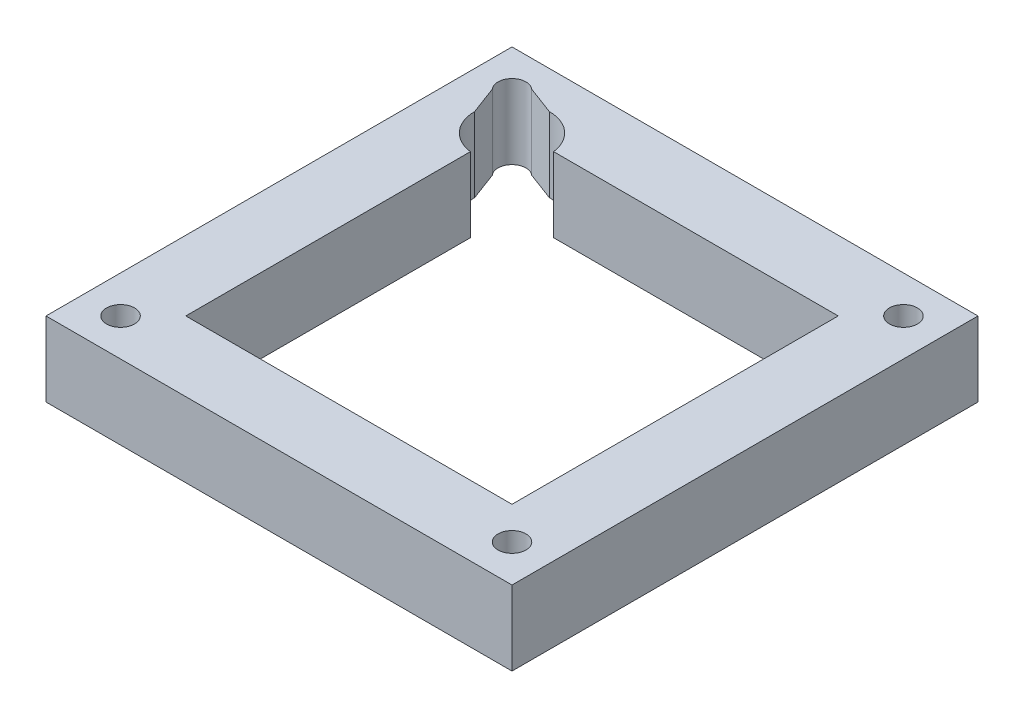
SolidWorks part; units mm, degrees
ref_plane "Front Plane" through (0, 0, 0) normal (0, 0, 1) x (1, 0, 0)
ref_plane "Top Plane" through (0, 0, 0) normal (0, 1, 0) x (1, 0, 0)
ref_plane "Right Plane" through (0, 0, 0) normal (1, 0, 0) x (0, 0, -1)
sketch "Sketch1" plane through (0, 0, 0) normal (0, 1, 0) x (1, 0, 0)
  line L0 (17.5, 17.5) -> (-13.0314, 17.5)
  line L1 (-25, -25) -> (25, -25)
  line L2 (-25, -25) -> (-25, 25)
  line L3 (-25, 25) -> (25, 25)
  line L4 (25, -25) -> (25, 25)
  line L5 (0, 25) -> (0, -25) construction
  line L6 (-25, 0) -> (25, 0) construction
  line L11 (0, 20) -> (0, -20) construction
  line L12 (-20, 0) -> (20, 0) construction
  line L13 (-17.5, -17.5) -> (17.5, -17.5)
  line L16 (17.5, -17.5) -> (17.5, 17.5)
  line L17 (0, 17.5) -> (0, -17.5) construction
  line L18 (-17.5, 0) -> (17.5, 0) construction
  line L19 (-17.5, -17.5) -> (-17.5, 13.0314)
  line L20 (-22.1301, 20.0137) -> (-21, 17)
  line L21 (-20.0137, 22.1301) -> (-17, 21)
  arc A0 (-20.0137, 22.1301) -> (-22.1301, 20.0137) centre (-21, 21) ccw
  circle A1 centre (21, 21) radius 1.5
  circle A2 centre (21, -21) radius 1.5
  circle A3 centre (-21, -21) radius 1.5
  arc A4 (-21, 17) -> (-17, 21) centre (-17, 17) ccw
  point P0 (0, 0)
  point P4 (0, 0)
  point P13 (0, 0)
  dimension "D1" = 50
  dimension "D2" = 50
  dimension "D4" = 35
extrude "Support" add sketch "Sketch1" along normal blind 8 contours L1 L4 L3 L2 A4 L0 L16 L13 L19 L20 A0 L21 A1 A2 A3
sketch "Sketch2" plane through (0, 0, 0) normal (0, 0, 1) x (1, 0, 0)
  line L4 (-10, 1.5) -> (10, 1.5)
  line L5 (-10, 1.5) -> (-10, 6.5)
  line L6 (-10, 6.5) -> (10, 6.5)
  line L7 (10, 1.5) -> (10, 6.5)
  line L8 (0, 6.5) -> (0, 1.5) construction
  line L9 (-10, 4) -> (10, 4) construction
  point P6 (0, 4)
  dimension "D1" = 20
  dimension "D2" = 5
sketch "Sketch3" plane through (0, 0, 0) normal (1, 0, 0) x (0, 0, -1)
  line L4 (-10, 1.5) -> (10, 1.5)
  line L5 (-10, 1.5) -> (-10, 6.5)
  line L6 (-10, 6.5) -> (10, 6.5)
  line L7 (10, 1.5) -> (10, 6.5)
  line L8 (0, 6.5) -> (0, 1.5) construction
  line L9 (-10, 4) -> (10, 4) construction
  point P6 (0, 4)
  dimension "D1" = 20
  dimension "D2" = 5
extrude "North Cut" cut sketch "Sketch2" along normal blind 4 from surface at -25 starting at face at (0, 4, -25)
extrude "West Cut" cut sketch "Sketch3" along normal blind 4 from surface at -25 starting at face at (-25, 4, 0)
